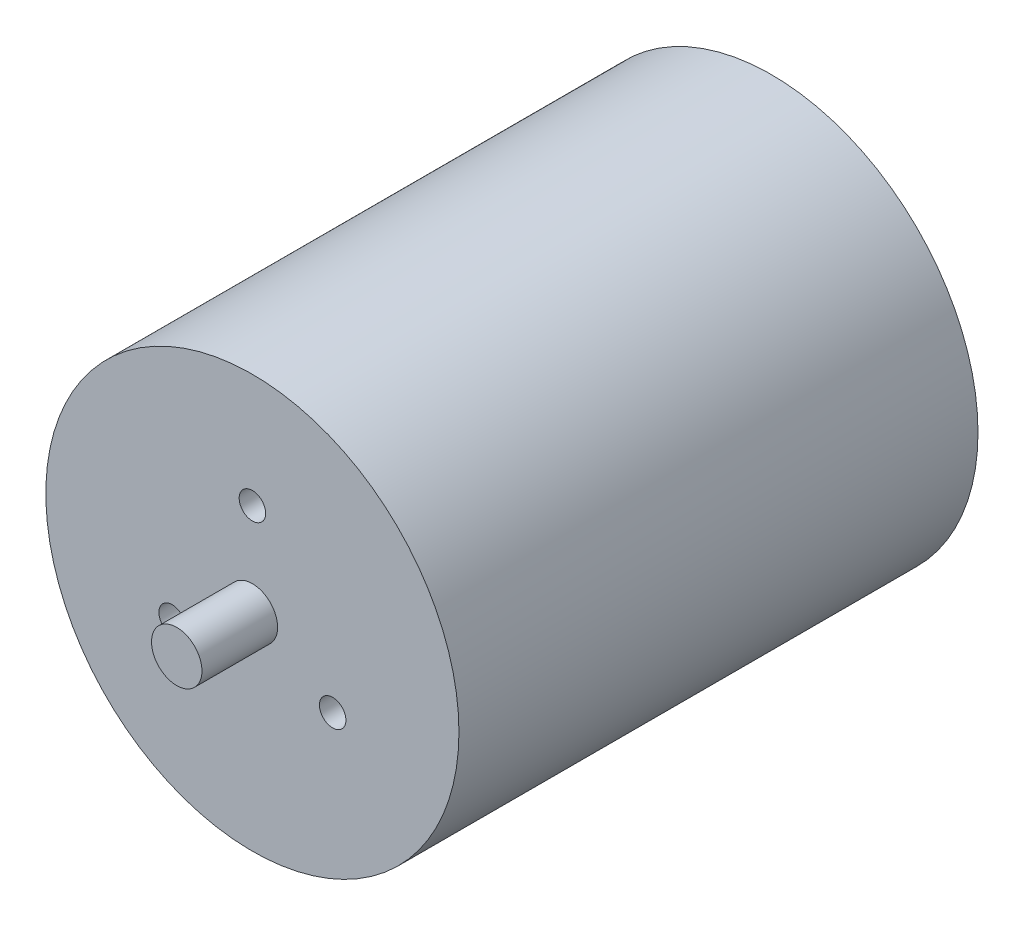
SolidWorks part; units mm, degrees
ref_plane "Front Plane" through (0, 0, 0) normal (0, 0, 1) x (1, 0, 0)
ref_plane "Top Plane" through (0, 0, 0) normal (0, 1, 0) x (1, 0, 0)
ref_plane "Right Plane" through (0, 0, 0) normal (1, 0, 0) x (0, 0, -1)
sketch "Sketch1" plane through (0, 0, 0) normal (0, 0, 1) x (1, 0, 0)
  circle A0 centre (0, 0) radius 39
  dimension "D1" = 78
extrude "Boss-Extrude1" add sketch "Sketch1" along normal blind 98
sketch "Sketch2" plane through (0, 0, 98) normal (0, 0, 1) x (1, 0, 0)
  circle A0 centre (0, 0) radius 4.7625
  dimension "D1" = 9.525
extrude "Boss-Extrude2" add sketch "Sketch2" along normal blind 14.2875
sketch "Sketch3" plane through (0, 0, 98) normal (0, 0, 1) x (1, 0, 0)
  circle A0 centre (0, 0) radius 17.5 construction
  circle A1 centre (0, 0) radius 39 construction
  point P3 (0, 17.5)
  point P7 (15.1554, -8.75)
  point P8 (-15.1554, -8.75)
  point P9 (0, 0)
  dimension "D1" = 35
  dimension "D2" = 3
hole_wizard "M6x1.0 Tapped Hole1" positions "Sketch5" profile "Sketch4" tap size "M6x1.0" standard "ANSI Metric"
sketch "Sketch5" plane through (0, 0, 98) normal (0, 0, 1) x (1, 0, 0)
  point P0 (0, 17.5)
  point P3 (15.1554, -8.75)
  point P6 (-15.1554, -8.75)
sketch "Sketch4" plane through (0, 17.5, 98) normal (1, 0, 0) x (0, -1, 0)
  line L0 (0, 0) -> (0, 16.5009)
  line L1 (0, 16.5009) -> (2.5, 14.9987)
  line L2 (2.5, 14.9987) -> (2.5, 0)
  line L5 (2.5, 0) -> (0, 0)
  line L10 (0, 16.5009) -> (-2.5, 14.9987) construction
  line L11 (0, -6.35) -> (0, 107.95) construction
  dimension "Tap Drill Dia." = 5
  dimension "Tap Drill Depth" = 14.9987
  dimension "Drill Angle" = 118
cosmetic thread "Hole Thread1" parameters "D1"=11.999, "D2"=6
cosmetic thread "Hole Thread2" parameters "D1"=11.999, "D2"=6
cosmetic thread "Hole Thread3" parameters "D1"=11.999, "D2"=6
